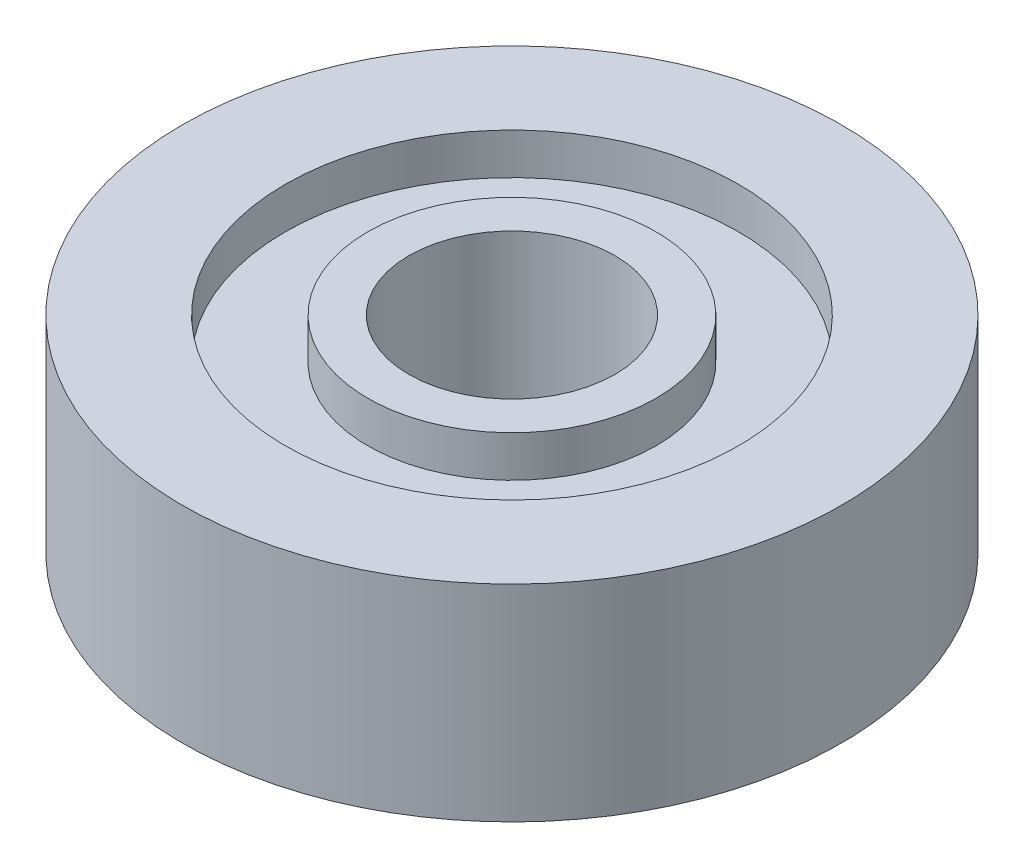
SolidWorks part; units mm, degrees
ref_plane "Front Plane" through (0, 0, 0) normal (0, 0, 1) x (1, 0, 0)
ref_plane "Top Plane" through (0, 0, 0) normal (0, 1, 0) x (1, 0, 0)
ref_plane "Right Plane" through (0, 0, 0) normal (1, 0, 0) x (0, 0, -1)
sketch "Sketch1" plane through (0, 0, 0) normal (0, 0, 1) x (1, 0, 0)
  line L0 (1.1027, 7.8696) -> (1.1027, -0.8389) construction
  line L2 (3.6027, -2.5) -> (4.6027, -2.5)
  line L3 (4.6027, -2.5) -> (4.6027, -1.5)
  line L4 (4.6027, 2.5) -> (3.6027, 2.5)
  line L5 (4.6027, 1.5) -> (6.6027, 1.5)
  line L6 (4.6027, -1.5) -> (6.6027, -1.5)
  line L9 (6.6027, 2.5) -> (6.6027, 1.5)
  line L11 (6.6027, -2.5) -> (6.6027, -1.5)
  line L12 (-3.3723, 0) -> (10.1415, 0) construction
  line L13 (3.6027, 2.5) -> (3.6027, -2.5)
  line L14 (4.6027, 1.5) -> (4.6027, 2.5)
  line L15 (6.6027, -2.5) -> (9.1027, -2.5)
  line L16 (9.1027, -2.5) -> (9.1027, 2.5)
  line L17 (9.1027, 2.5) -> (6.6027, 2.5)
  dimension "D1" = 2.5
  dimension "D2" = 8
  dimension "D3" = 2.5
  dimension "D4" = 2.5
  dimension "D5" = 1
  dimension "D6" = 1
  dimension "D8" = 1
  dimension "2" = 2
revolve "Revolve1" add sketch "Sketch1" angle 360 about L0
